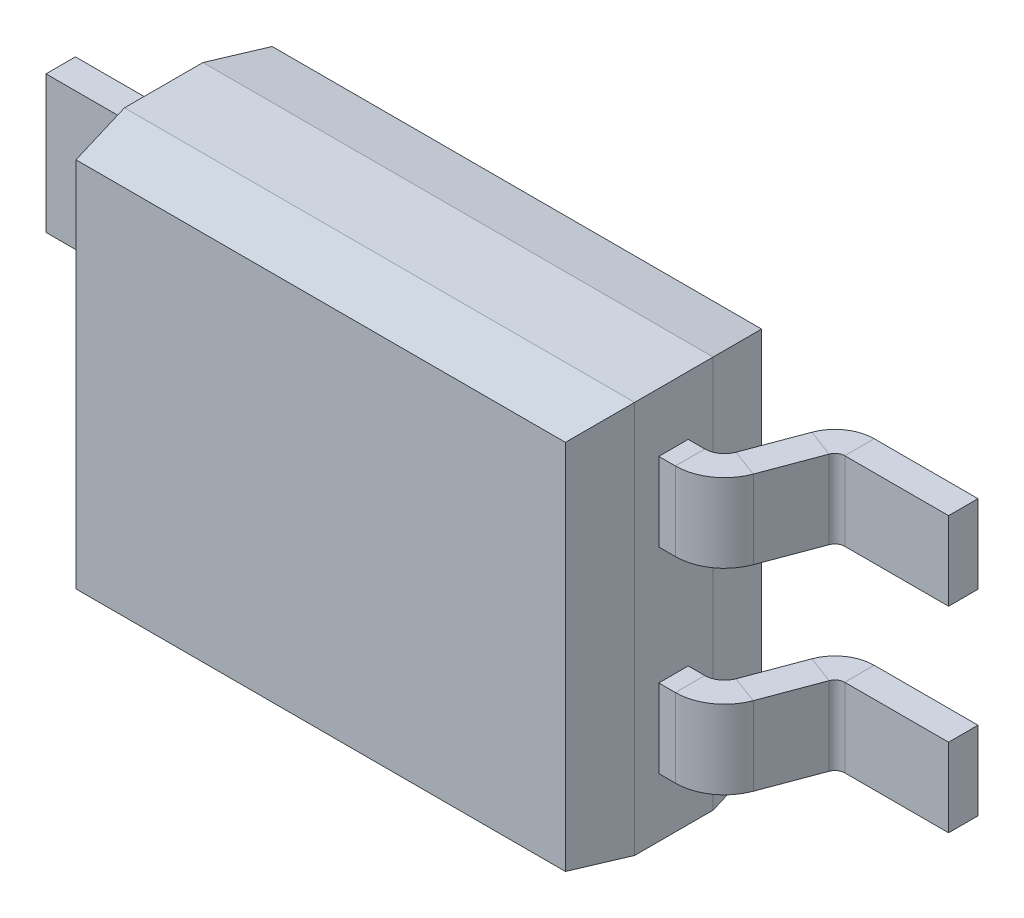
SolidWorks part; units mm, degrees
ref_plane "Front Plane" through (0, 0, 0) normal (0, 0, 1) x (1, 0, 0)
ref_plane "Top Plane" through (0, 0, 0) normal (0, 1, 0) x (1, 0, 0)
ref_plane "Right Plane" through (0, 0, 0) normal (1, 0, 0) x (0, 0, -1)
sketch "Sketch1" plane through (0, 0, 0) normal (0, 0, 1) x (1, 0, 0)
  line L1 (-1.3, -1) -> (1.3, -1)
  line L2 (-1.3, -1) -> (-1.3, 1)
  line L3 (-1.3, 1) -> (1.3, 1)
  line L4 (1.3, -1) -> (1.3, 1)
  line L5 (-1.3, -1) -> (1.3, 1) construction
  line L6 (-1.3, 1) -> (1.3, -1) construction
  point P0 (0, 0)
  dimension "D1" = 2.6
  dimension "D2" = 2
extrude "Boss-Extrude1" add sketch "Sketch1" along normal blind 1 contours L2 L3 L4 L1
ref_plane "Plane1" through (-2.3, 0, 0) normal (-1, 0, 0) x (0, 0, 1)
sketch "Sketch2" plane through (-2.3, 0, 0) normal (-1, 0, 0) x (0, 0, 1)
  line L0 (0, -1) -> (0, 1) construction
  line L1 (-0.05, -0.35) -> (0.1, -0.35)
  line L2 (-0.05, -0.35) -> (-0.05, 0.35)
  line L3 (-0.05, 0.35) -> (0.1, 0.35)
  line L4 (0.1, -0.35) -> (0.1, 0.35)
  line L5 (-0.05, -0.35) -> (0.1, 0.35) construction
  line L6 (-0.05, 0.35) -> (0.1, -0.35) construction
  point P0 (0.025, 0)
  point P7 (0, 0)
  dimension "D1" = 0.05
  dimension "D2" = 0.15
  dimension "D3" = 0.7
sketch "Sketch3" plane through (0, 0, 0) normal (0, 1, 0) x (1, 0, 0)
  line L0 (-2.3, -0.025) -> (-1.7944, -0.025)
  line L1 (-1.6511, -0.1307) -> (-1.5768, -0.3712)
  line L2 (-1.4335, -0.4769) -> (-0.4262, -0.4769)
  arc A0 (-1.7944, -0.025) -> (-1.6511, -0.1307) centre (-1.7944, -0.175) cw
  arc A1 (-1.5768, -0.3712) -> (-1.4335, -0.4769) centre (-1.4335, -0.3269) ccw
  dimension "D1" = 0.15
sweep "Sweep1" add profiles "Sketch2" path "Sketch3"
ref_plane "Plane2" through (2.3, 0, 0) normal (1, 0, 0) x (0, 0, -1)
sketch "Sketch4" plane through (2.3, 0, 0) normal (1, 0, 0) x (0, 0, -1)
  line L0 (0.05, 0.35) -> (0.05, -0.35) construction
  line L1 (0.05, -0.7) -> (-0.1, -0.7)
  line L2 (0.05, -0.7) -> (0.05, -0.3)
  line L3 (0.05, -0.3) -> (-0.1, -0.3)
  line L4 (-0.1, -0.7) -> (-0.1, -0.3)
  line L5 (0.05, -0.7) -> (-0.1, -0.3) construction
  line L6 (0.05, -0.3) -> (-0.1, -0.7) construction
  line L7 (-0.1, -0.35) -> (-0.1, 0.35) construction
  point P0 (-0.025, -0.5)
  point P10 (0, 0)
  dimension "D1" = 0.4
  dimension "D2" = 0.5
ref_plane "Plane3" through (0, -0.5, 0) normal (0, -1, 0) x (-1, 0, 0)
sketch "Sketch5" plane through (0, -0.5, 0) normal (0, 1, 0) x (1, 0, 0)
  line L0 (3.1383, 0) -> (1.7709, 0)
  line L1 (1.6304, -0.0976) -> (1.5252, -0.3793)
  line L2 (1.3847, -0.4769) -> (0.6315, -0.4769)
  line L3 (-1.4335, -0.4769) -> (-0.4262, -0.4769) construction
  arc A0 (1.7709, 0) -> (1.6304, -0.0976) centre (1.7709, -0.15) ccw
  arc A1 (1.5252, -0.3793) -> (1.3847, -0.4769) centre (1.3847, -0.3269) cw
  point P7 (0, 0)
  point P12 (3.1383, 0)
  dimension "D1" = 0.15
sweep "Sweep3" add profiles "Sketch4" path "Sketch5"
pattern_linear "LPattern1" count 2 spacing 1 along (0, 1, 0) of "Sweep3"
chamfer "Chamfer1" distance 0.3 angle 10 4 edges at (1.3, 0, 1) (0, 1, 1) (0, -1, 1) (-1.3, 0, 1)
chamfer "Chamfer3" distance 0.3 angle 10 4 edges at (-1.3, 0, 0) (0, -1, 0) (1.3, 0, 0) (0, 1, 0)
